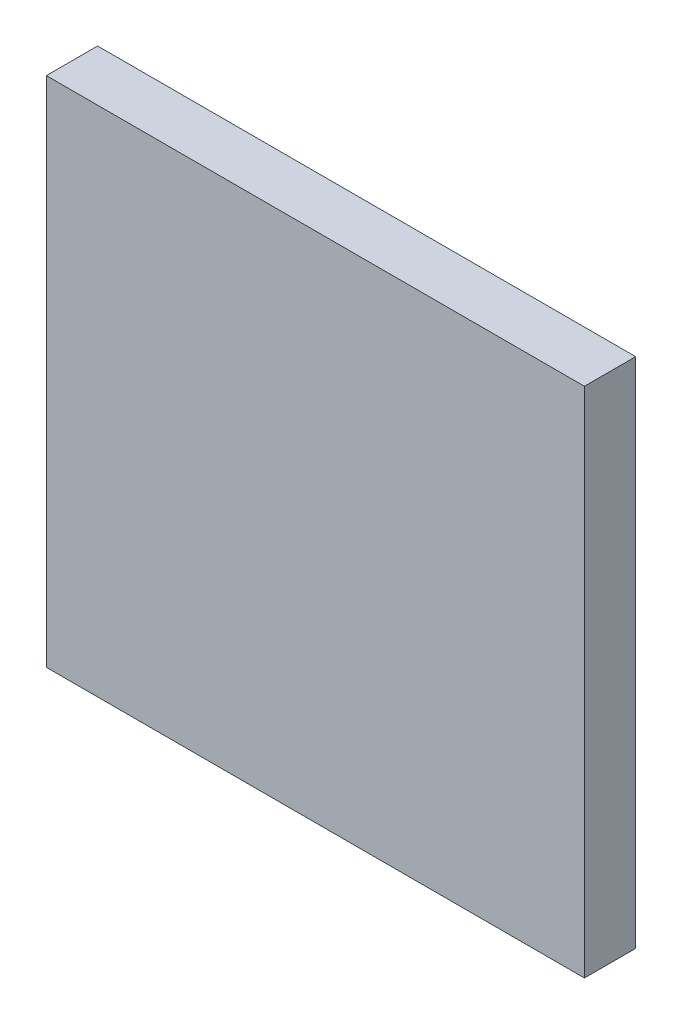
SolidWorks part; units mm, degrees
material "Простая углеродистая сталь"
ref_plane "Спереди" through (0, 0, 0) normal (0, 0, 1) x (1, 0, 0)
ref_plane "Сверху" through (0, 0, 0) normal (0, 1, 0) x (1, 0, 0)
ref_plane "Справа" through (0, 0, 0) normal (1, 0, 0) x (0, 0, -1)
sketch "Эскиз1" plane through (0, 0, 0) normal (0, 0, 1) x (1, 0, 0)
  line L1 (0, 0) -> (1050, 0)
  line L2 (0, 0) -> (0, -1000)
  line L3 (0, -1000) -> (1050, -1000)
  line L4 (1050, 0) -> (1050, -1000)
  line L5 (525, -1000) -> (525, 0) construction
  line L6 (0, -500) -> (1050, -500) construction
  point P88 (525, -500)
  dimension "D1" = 1050
  dimension "D2" = 1000
extrude "Бобышка-Вытянуть1" add sketch "Эскиз1" along normal blind 100
